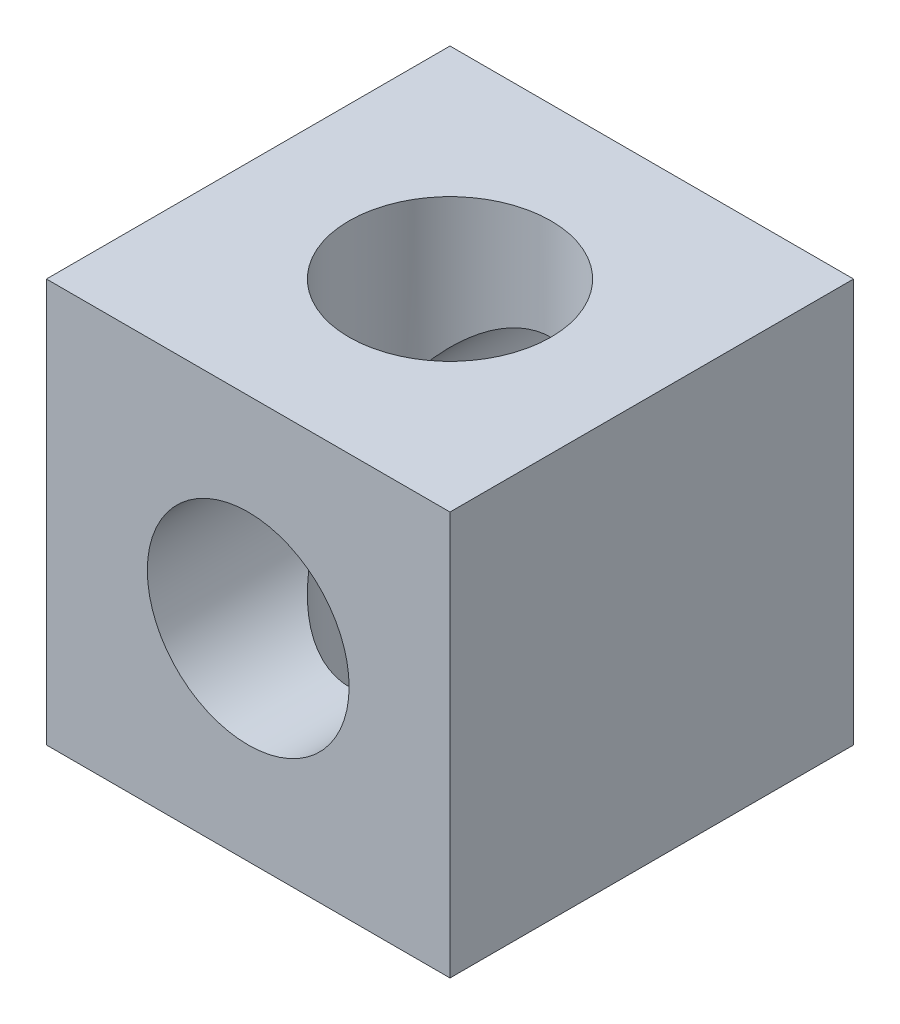
SolidWorks part; units mm, degrees
ref_plane "前视基准面" through (0, 0, 0) normal (0, 0, 1) x (1, 0, 0)
ref_plane "上视基准面" through (0, 0, 0) normal (0, 1, 0) x (1, 0, 0)
ref_plane "右视基准面" through (0, 0, 0) normal (1, 0, 0) x (0, 0, -1)
sketch "草图1" plane through (0, 0, 0) normal (0, 0, 1) x (1, 0, 0)
  line L1 (-4, 4) -> (4, 4)
  line L2 (-4, 4) -> (-4, -4)
  line L3 (-4, -4) -> (4, -4)
  line L4 (4, 4) -> (4, -4)
  dimension "D1" = 8
  dimension "D2" = 8
  dimension "D3" = 4
  dimension "D4" = 4
extrude "拉伸1" add sketch "草图1" along normal blind 8
sketch "草图2" plane through (0, 0, 8) normal (0, 0, 1) x (1, 0, 0)
  circle A0 centre (0, 0) radius 2
  dimension "D1" = 4
extrude "切除-拉伸1" cut sketch "草图2" against normal blind 22
sketch "草图3" plane through (0, 4, 0) normal (0, 1, 0) x (-1, 0, 0)
  circle A0 centre (0, 4) radius 2
  dimension "D1" = 4
extrude "切除-拉伸2" cut sketch "草图3" against normal blind 22
